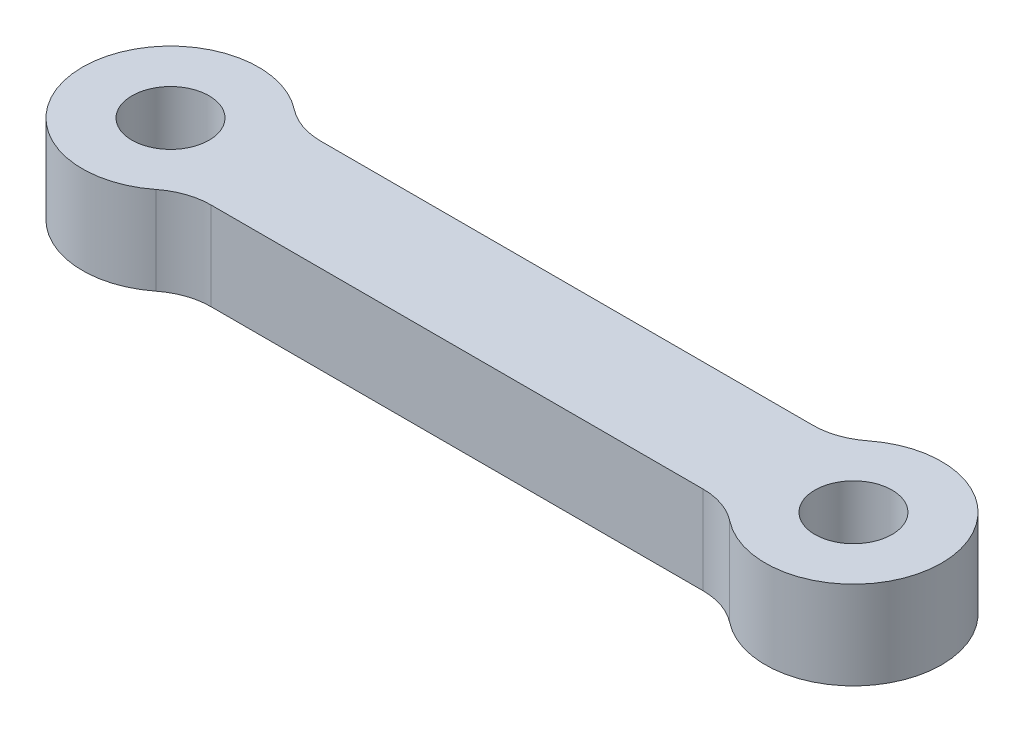
SolidWorks part; units mm, degrees
ref_plane "Front Plane" through (0, 0, 0) normal (0, 0, 1) x (1, 0, 0)
ref_plane "Top Plane" through (0, 0, 0) normal (0, 1, 0) x (1, 0, 0)
ref_plane "Right Plane" through (0, 0, 0) normal (1, 0, 0) x (0, 0, -1)
sketch "Sketch1" plane through (0, 0, 0) normal (0, 1, 0) x (1, 0, 0)
  line L0 (3.1225, 2.5) -> (27.8775, 2.5)
  line L1 (31, 0) -> (0, 0) construction
  line L2 (3.1225, -2.5) -> (27.8775, -2.5)
  circle A0 centre (0, 0) radius 1.75
  circle A2 centre (0, 0) radius 4
  circle A3 centre (31, 0) radius 1.75
  circle A4 centre (31, 0) radius 4
  dimension "D1" = 3.5
  dimension "D2" = 31
  dimension "D3" = 8
  dimension "D4" = 5
extrude "Boss-Extrude1" add sketch "Sketch1" along normal blind 4
fillet "Fillet1" radius 3 4 edges at (3.1225, 2, -2.5) (3.1225, 2, 2.5) (27.8775, 2, -2.5) (27.8775, 2, 2.5)
